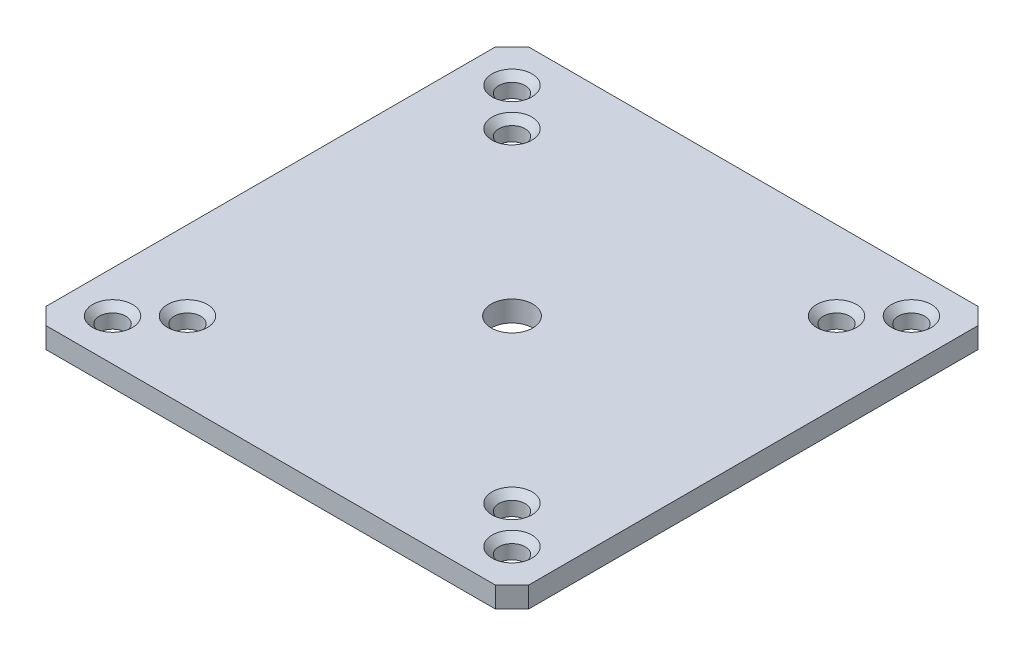
SolidWorks part; units mm, degrees
ref_plane "Front Plane" through (0, 0, 0) normal (0, 0, 1) x (1, 0, 0)
ref_plane "Top Plane" through (0, 0, 0) normal (0, 1, 0) x (1, 0, 0)
ref_plane "Right Plane" through (0, 0, 0) normal (1, 0, 0) x (0, 0, -1)
sketch "Sketch1" plane through (0, 0, 0) normal (0, 1, 0) x (1, 0, 0)
  line L1 (36.83, -36.83) -> (-36.83, -36.83)
  line L2 (36.83, -36.83) -> (36.83, 36.83)
  line L3 (36.83, 36.83) -> (-36.83, 36.83)
  line L4 (-36.83, -36.83) -> (-36.83, 36.83)
  line L5 (36.83, -36.83) -> (-36.83, 36.83) construction
  line L6 (36.83, 36.83) -> (-36.83, -36.83) construction
  circle A0 centre (0, 0) radius 3.175
  point P0 (0, 0)
  dimension "D3" = 6.35
  dimension "D1" = 73.66
  dimension "D2" = 73.66
extrude "Boss-Extrude1" add sketch "Sketch1" along normal blind 3.175
chamfer "Chamfer2" distance 2.54 angle 45 4 edges at (36.83, 1.5875, -36.83) (-36.83, 1.5875, -36.83) (-36.83, 1.5875, 36.83) (36.83, 1.5875, 36.83)
sketch "Sketch2" plane through (0, 3.175, 0) normal (0, 1, 0) x (1, 0, 0)
  line L0 (-1.7463, 0) -> (1.7463, 0) construction
  line L1 (0, -1.7463) -> (0, 1.7463) construction
  point P0 (30.48, 30.48)
  point P1 (-30.48, 30.48)
  point P4 (-30.48, -30.48)
  point P5 (30.48, -30.48)
  dimension "D1" = 60.96
  dimension "D2" = 60.96
  dimension "D3" = 30.48
hole_wizard "#10-32 Tapped Hole1" positions "Sketch2" profile "Sketch3" tap size "#10-32" standard "ANSI Inch" end condition up to next
sketch "Sketch3" plane through (30.48, 3.175, -30.48) normal (1, 0, 0) x (0, 0, 1)
  line L0 (0, 0) -> (0, 3.175)
  line L1 (0, 3.175) -> (2.0193, 3.175)
  line L2 (2.0193, 3.175) -> (2.0193, 1.0287)
  line L3 (2.0193, 1.0287) -> (3.048, 0)
  line L5 (3.048, 0) -> (0, 0)
  line L6 (-2.0193, 1.0287) -> (-3.048, 0) construction
  line L11 (0, -6.35) -> (0, 107.95) construction
  dimension "Thru Tap Drill Dia." = 4.0386
  dimension "Thru Tap Drill Depth" = 3.175
  dimension "Near C'Sink Dia." = 6.096
  dimension "Near C'Sink Angle" = 90
cosmetic thread "Hole Thread1" parameters "D2"=4.826
cosmetic thread "Hole Thread2" parameters "D2"=4.826
cosmetic thread "Hole Thread3" parameters "D2"=4.826
cosmetic thread "Hole Thread4" parameters "D2"=4.826
sketch "Sketch4" plane through (0, 3.175, 0) normal (0, 1, 0) x (1, 0, 0)
  line L0 (-1.7463, 0) -> (1.7463, 0) construction
  line L1 (0, -1.7463) -> (0, 1.7463) construction
  point P0 (-24.765, 24.765)
  point P1 (24.765, 24.765)
  point P4 (-24.765, -24.765)
  point P5 (24.765, -24.765)
  dimension "D1" = 49.53
  dimension "D2" = 49.53
  dimension "D3" = 24.765
hole_wizard "#10-32 Tapped Hole2" positions "Sketch4" profile "Sketch5" tap size "#10-32" standard "ANSI Inch" end condition through all
sketch "Sketch5" plane through (-24.765, 3.175, -24.765) normal (1, 0, 0) x (0, 0, 1)
  line L0 (0, 0) -> (0, 3.175)
  line L1 (0, 3.175) -> (2.0193, 3.175)
  line L2 (2.0193, 3.175) -> (2.0193, 1.0287)
  line L3 (2.0193, 1.0287) -> (3.048, 0)
  line L5 (3.048, 0) -> (0, 0)
  line L6 (-2.0193, 1.0287) -> (-3.048, 0) construction
  line L11 (0, -6.35) -> (0, 107.95) construction
  dimension "Thru Tap Drill Dia." = 4.0386
  dimension "Thru Tap Drill Depth" = 3.175
  dimension "Near C'Sink Dia." = 6.096
  dimension "Near C'Sink Angle" = 90
cosmetic thread "Hole Thread5" parameters "D2"=4.826
cosmetic thread "Hole Thread6" parameters "D2"=4.826
cosmetic thread "Hole Thread7" parameters "D2"=4.826
cosmetic thread "Hole Thread8" parameters "D2"=4.826
